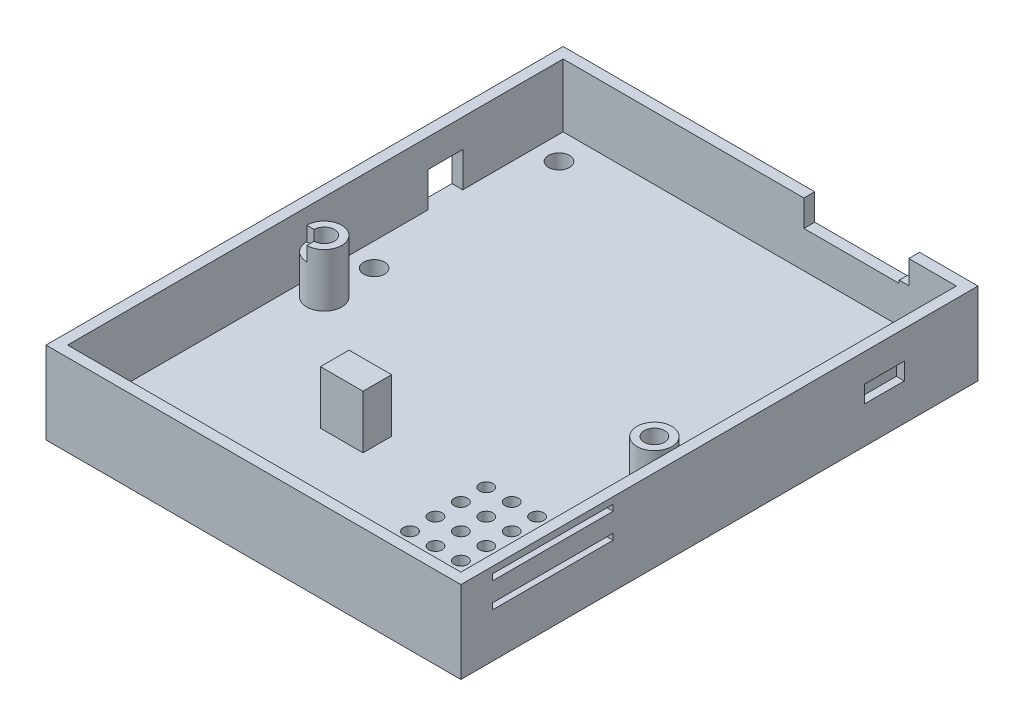
SolidWorks part; units mm, degrees
ref_plane "Front Plane" through (0, 0, 0) normal (0, 0, 1) x (1, 0, 0)
ref_plane "Top Plane" through (0, 0, 0) normal (0, 1, 0) x (1, 0, 0)
ref_plane "Right Plane" through (0, 0, 0) normal (1, 0, 0) x (0, 0, -1)
sketch "Sketch2" plane through (0, 0, 0) normal (0, 1, 0) x (1, 0, 0)
  line L1 (-51.1166, -72.3688) -> (14.1834, -72.3688)
  line L2 (-51.1166, -72.3688) -> (-51.1166, 9.0312)
  line L3 (-51.1166, 9.0312) -> (14.1834, 9.0312)
  line L4 (14.1834, -72.3688) -> (14.1834, 9.0312)
  dimension "D1" = 65.3
  dimension "D2" = 81.4
extrude "Boss-Extrude1" add sketch "Sketch2" along normal blind 3
sketch "Sketch3" plane through (0, 3, 0) normal (0, 1, 0) x (1, 0, 0)
  line L0 (-49.4166, -70.6688) -> (-49.4166, 7.3312)
  line L1 (-49.4166, 7.3312) -> (12.4834, 7.3312)
  line L2 (12.4834, 7.3312) -> (12.4834, -70.6688)
  line L3 (12.4834, -70.6688) -> (-49.4166, -70.6688)
  line L4 (-51.1166, -72.3688) -> (-51.1166, 9.0312)
  line L5 (-51.1166, 9.0312) -> (14.1834, 9.0312)
  line L6 (14.1834, 9.0312) -> (14.1834, -72.3688)
  line L7 (14.1834, -72.3688) -> (-51.1166, -72.3688)
  dimension "D1" = 1.7
  dimension "D2" = 1.7
  dimension "D3" = 1.7
  dimension "D4" = 1.7
extrude "Boss-Extrude2" add sketch "Sketch3" along normal blind 9.94
sketch "Sketch4" plane through (0, 3, 0) normal (0, 1, 0) x (1, 0, 0)
  line L0 (-45.7166, -26.1188) -> (-45.7166, 2.9812) construction
  line L1 (-28.1166, -47.6688) -> (-21.4166, -47.6688)
  line L2 (-28.1166, -47.6688) -> (-28.1166, -52.1688)
  line L3 (-28.1166, -52.1688) -> (-21.4166, -52.1688)
  line L4 (-21.4166, -47.6688) -> (-21.4166, -52.1688)
  line L5 (-45.7166, 2.9812) -> (7.4834, 2.9812) construction
  line L6 (7.4834, 2.9812) -> (7.4834, -26.1188) construction
  line L7 (7.4834, -26.1188) -> (-45.7166, -26.1188) construction
  line L8 (-49.4166, 7.3312) -> (-49.4166, -70.6688) construction
  line L9 (12.4834, 7.3312) -> (-49.4166, 7.3312) construction
  line L13 (-49.4166, 7.3312) -> (-49.4166, -70.6688) construction
  line L14 (-49.4166, -70.6688) -> (12.4834, -70.6688) construction
  circle A0 centre (-45.7166, 2.9812) radius 1.65
  circle A1 centre (-45.7166, -26.1188) radius 1.65
  circle A2 centre (7.4834, 2.9812) radius 1.65
  circle A3 centre (7.4834, -26.1188) radius 1.65
  circle A4 centre (-45.7166, -33.9688) radius 1.6
  circle A5 centre (7.6777, -35.3988) radius 1.6
  dimension "D5" = 3.3
  dimension "D12" = 3.2
  dimension "D1" = 29.1
  dimension "D2" = 53.2
  dimension "D3" = 3.7
  dimension "D4" = 4.35
  dimension "D6" = 28
  dimension "D7" = 23
  dimension "D8" = 6.7
  dimension "D9" = 4.5
  dimension "D10" = 7.85
  dimension "D11" = 53.3943
  dimension "D13" = 38.38
extrude "Cut-Extrude1" cut sketch "Sketch4" against normal through all
sketch "Sketch5" plane through (0, 3, 0) normal (0, 1, 0) x (1, 0, 0)
  line L1 (-28.1166, -52.1688) -> (-21.4166, -52.1688)
  line L2 (-28.1166, -52.1688) -> (-28.1166, -47.6688)
  line L3 (-28.1166, -47.6688) -> (-21.4166, -47.6688)
  line L4 (-21.4166, -52.1688) -> (-21.4166, -47.6688)
extrude "Boss-Extrude3" add sketch "Sketch5" along normal blind 10.15 and the other way up to surface (3 mm away) separate body other way up to face at (7.6777, 0, 36.9988)
sketch "Sketch6" plane through (0, 3, 0) normal (0, 1, 0) x (1, 0, 0)
  circle A0 centre (-45.7166, -33.9688) radius 2.75
  circle A1 centre (7.6777, -35.3988) radius 2.75
  circle A2 centre (-45.7166, -33.9688) radius 1.6 construction
  circle A3 centre (7.6777, -35.3988) radius 1.6 construction
  dimension "D1" = 5.5
extrude "Boss-Extrude4" add sketch "Sketch6" along normal blind 10.15 separate body
sketch "Sketch7" plane through (0, 13.15, 0) normal (0, 1, 0) x (1, 0, 0)
  line L0 (-48.4666, -33.9688) -> (-45.7166, -33.9688)
  line L1 (-45.7166, -33.9688) -> (-45.7166, -36.7188)
  arc A0 (-48.4666, -33.9688) -> (-45.7166, -36.7188) centre (-45.7166, -33.9688) ccw
  circle A3 centre (-45.7166, -33.9688) radius 2.75 construction
extrude "Cut-Extrude2" cut sketch "Sketch7" against normal blind 4
sketch "Sketch17" plane through (0, 13.15, 0) normal (0, 1, 0) x (1, 0, 0)
  circle A0 centre (-45.7166, -33.9688) radius 1.6
  circle A1 centre (7.6777, -35.3988) radius 1.6
  circle A2 centre (7.6777, -35.3988) radius 2.75 construction
  dimension "D1" = 3.2
extrude "Cut-Extrude11" cut sketch "Sketch17" against normal through all
sketch "Sketch19" plane through (-49.4166, 0, 0) normal (1, 0, 0) x (0, 0, -1)
  line L0 (7.3312, 3) -> (-70.6688, 3) construction
  line L1 (-13.9688, 3) -> (-8.4688, 3)
  line L2 (-13.9688, 3) -> (-13.9688, 8.5)
  line L3 (-13.9688, 8.5) -> (-8.4688, 8.5)
  line L4 (-8.4688, 3) -> (-8.4688, 8.5)
  line L5 (-11.2188, 8.5) -> (-11.2188, 3) construction
  line L7 (7.3312, 12.94) -> (7.3312, 3) construction
  dimension "D1" = 5.5
  dimension "D2" = 15.8
  dimension "D3" = 5.5
extrude "Cut-Extrude12" cut sketch "Sketch19" against normal through all
sketch "Sketch20" plane through (0, 0, -7.3312) normal (0, 0, 1) x (1, 0, 0)
  line L0 (12.4834, 12.94) -> (-49.4166, 12.94) construction
  line L1 (-11.5166, 12.94) -> (3.4834, 12.94)
  line L2 (-11.5166, 12.94) -> (-11.5166, 8.79)
  line L3 (-11.5166, 8.79) -> (3.4834, 8.79)
  line L4 (3.4834, 12.94) -> (3.4834, 8.79)
  dimension "D1" = 9
  dimension "D2" = 15
  dimension "D3" = 4.15
extrude "Cut-Extrude13" cut sketch "Sketch20" against normal through all
sketch "Sketch21" plane through (0, 13.15, 0) normal (0, 1, 0) x (1, 0, 0)
  circle A0 centre (-45.7166, -33.9688) radius 2.75
  arc A1 (-45.7166, -36.7188) -> (-48.4666, -33.9688) centre (-45.7166, -33.9688) ccw construction
extrude "Cut-Extrude14" cut sketch "Sketch21" against normal blind 1.75
sketch "Sketch22" plane through (0, 13.15, 0) normal (0, 1, 0) x (1, 0, 0)
  circle A0 centre (7.6777, -35.3988) radius 2.75
  circle A1 centre (7.6777, -35.3988) radius 1.6 construction
  circle A2 centre (7.6777, -35.3988) radius 2.75 construction
extrude "Cut-Extrude15" cut sketch "Sketch22" against normal blind 1.75
sketch "Sketch23" plane through (0, 13.15, 0) normal (0, 1, 0) x (1, 0, 0)
  line L1 (-28.1166, -52.1688) -> (-21.4166, -52.1688)
  line L2 (-28.1166, -52.1688) -> (-28.1166, -47.6688)
  line L3 (-28.1166, -47.6688) -> (-21.4166, -47.6688)
  line L4 (-21.4166, -52.1688) -> (-21.4166, -47.6688)
extrude "Cut-Extrude16" cut sketch "Sketch23" against normal blind 1.75
sketch "Sketch10" plane through (0, 3, 0) normal (0, 1, 0) x (1, 0, 0)
  circle A0 centre (-7.0166, -47.1688) radius 1.05
  circle A1 centre (-3.0166, -47.1688) radius 1.05
  circle A2 centre (0.9834, -47.1688) radius 1.05
  circle A3 centre (4.9834, -47.1688) radius 1.05
  circle A4 centre (8.9834, -47.1688) radius 1.05
  circle A5 centre (-3.0166, -51.1688) radius 1.05
  circle A6 centre (0.9834, -51.1688) radius 1.05
  circle A7 centre (4.9834, -51.1688) radius 1.05
  circle A8 centre (8.9834, -51.1688) radius 1.05
  circle A9 centre (-3.0166, -55.1688) radius 1.05
  circle A10 centre (0.9834, -55.1688) radius 1.05
  circle A11 centre (4.9834, -55.1688) radius 1.05
  circle A12 centre (8.9834, -55.1688) radius 1.05
  circle A13 centre (-3.0166, -59.1688) radius 1.05
  circle A14 centre (0.9834, -59.1688) radius 1.05
  circle A15 centre (4.9834, -59.1688) radius 1.05
  circle A16 centre (8.9834, -59.1688) radius 1.05
  circle A17 centre (-7.0166, -51.1688) radius 1.05
  circle A18 centre (-7.0166, -55.1688) radius 1.05
  circle A19 centre (-7.0166, -59.1688) radius 1.05
  dimension "D3" = 2.1
  dimension "D1" = 5
  dimension "D2" = 4
extrude "Cut-Extrude5" cut sketch "Sketch10" against normal through all
sketch "Sketch11" plane through (14.1834, 0, 0) normal (1, 0, 0) x (0, 0, -1)
  line L0 (9.0312, 12.94) -> (9.0312, 0) construction
  line L1 (-8.8688, 5.8) -> (-2.5688, 5.8)
  line L2 (-8.8688, 5.8) -> (-8.8688, 8.5)
  line L3 (-8.8688, 8.5) -> (-2.5688, 8.5)
  line L4 (-2.5688, 5.8) -> (-2.5688, 8.5)
  line L5 (-72.3688, 0) -> (9.0312, 0) construction
  dimension "D1" = 11.6
  dimension "D2" = 6.3
  dimension "D3" = 2.7
  dimension "D4" = 5.8
extrude "Cut-Extrude6" cut sketch "Sketch11" against normal blind 1.25
sketch "Sketch15" plane through (0, 0, -7.3312) normal (0, 0, 1) x (1, 0, 0)
  line L0 (12.4834, 12.94) -> (3.4834, 12.94) construction
  line L1 (-11.1166, 12.94) -> (4.9834, 12.94)
  line L2 (-11.1166, 12.94) -> (-11.1166, 9.24)
  line L3 (-11.1166, 9.24) -> (4.9834, 9.24)
  line L4 (4.9834, 12.94) -> (4.9834, 9.24)
  dimension "D1" = 7.5
  dimension "D2" = 16.1
  dimension "D3" = 3.7
extrude "Cut-Extrude9" cut sketch "Sketch15" against normal through all
sketch "Sketch16" plane through (14.1834, 0, 0) normal (1, 0, 0) x (0, 0, -1)
  line L0 (-72.3688, 0) -> (9.0312, 0) construction
  line L1 (-67.3688, 11.9101) -> (-48.4126, 11.9101)
  line L2 (-67.3688, 11.9101) -> (-67.3688, 10.9551)
  line L3 (-67.3688, 10.9551) -> (-48.4126, 10.9551)
  line L4 (-48.4126, 11.9101) -> (-48.4126, 10.9551)
  line L5 (-67.3688, 7.9551) -> (-48.4126, 7.9551)
  line L6 (-67.3688, 7.9551) -> (-67.3688, 7)
  line L7 (-67.3688, 7) -> (-48.4126, 7)
  line L8 (-48.4126, 7.9551) -> (-48.4126, 7)
  line L9 (-72.3688, 12.94) -> (-72.3688, 0) construction
  dimension "D1" = 3
  dimension "D2" = 7
  dimension "D3" = 5
extrude "Cut-Extrude10" cut sketch "Sketch16" against normal up to surface (1.7 mm away) up to face at (12.4834, 7.97, 31.6688)
